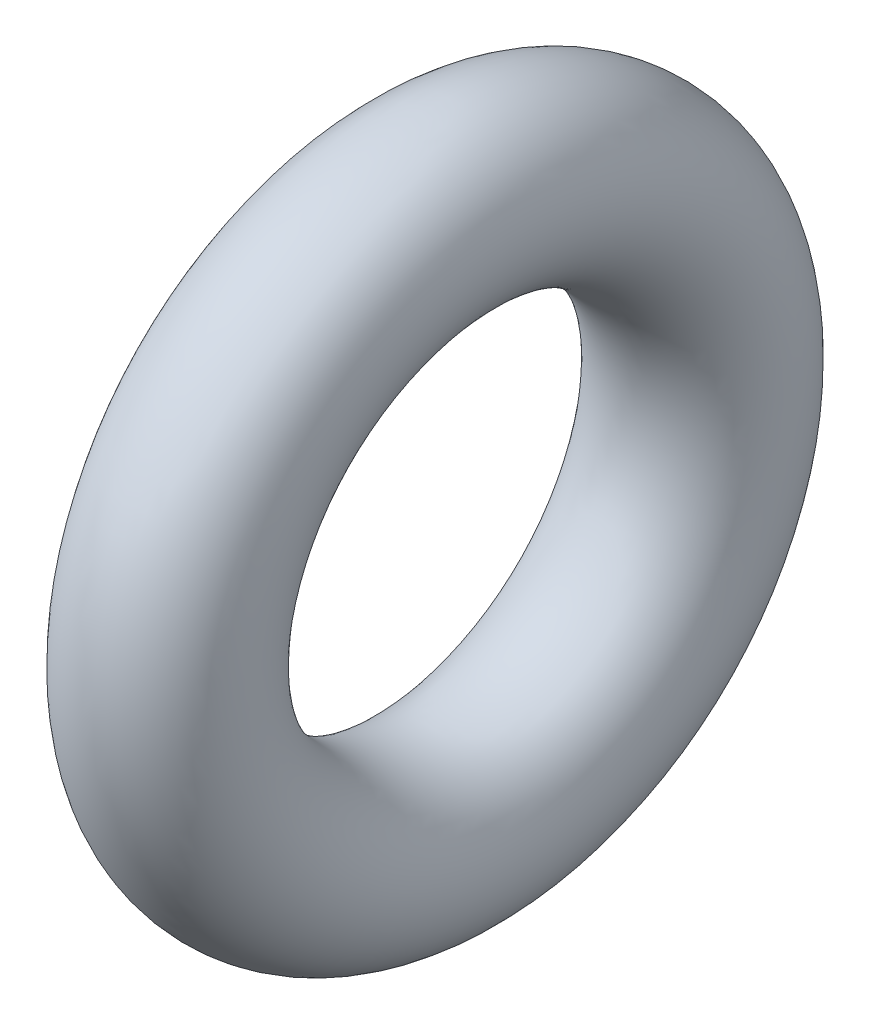
SolidWorks part; units mm, degrees
ref_plane "Front Plane" through (0, 0, 0) normal (0, 0, 1) x (1, 0, 0)
ref_plane "Top Plane" through (0, 0, 0) normal (0, 1, 0) x (1, 0, 0)
ref_plane "Right Plane" through (0, 0, 0) normal (1, 0, 0) x (0, 0, -1)
sketch "Sketch1" plane through (0, 0, 0) normal (0, 0, 1) x (1, 0, 0)
  line L0 (-9.6179, 0) -> (14.3938, 0) construction
  circle A0 centre (0, 21.9) radius 7
  dimension "D1" = 14
  dimension "D2" = 21.9
revolve "Revolve1" add sketch "Sketch1" angle 360 about L0
